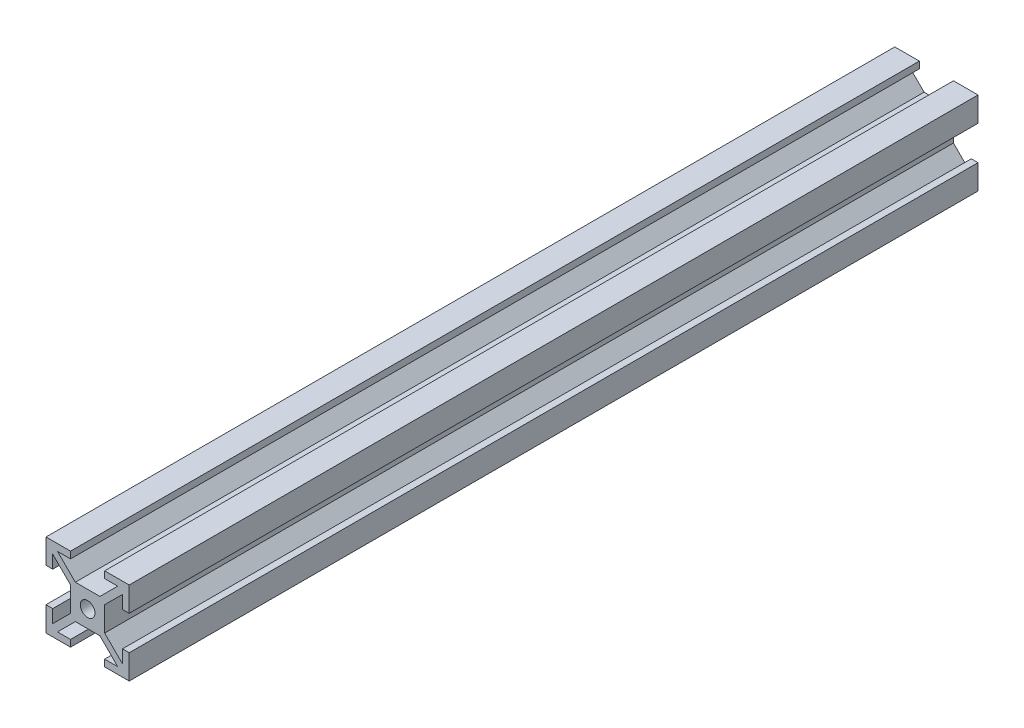
SolidWorks part; units mm, degrees
ref_plane "Front Plane" through (0, 0, 0) normal (0, 0, 1) x (1, 0, 0)
ref_plane "Top Plane" through (0, 0, 0) normal (0, 1, 0) x (1, 0, 0)
ref_plane "Right Plane" through (0, 0, 0) normal (1, 0, 0) x (0, 0, -1)
sketch "Sketch1" plane through (0, 0, 0) normal (0, 0, 1) x (1, 0, 0)
  line L0 (-8.38, 4.1) -> (-10, 4.1)
  line L1 (-2.9545, 4.1) -> (2.9545, 4.1)
  line L2 (-4.1, 2.9545) -> (-4.1, -2.9545)
  line L3 (-2.9545, -4.1) -> (2.9545, -4.1)
  line L4 (4.1, 2.9545) -> (4.1, -2.9545)
  line L5 (-4.1, 4.1) -> (4.1, -4.1) construction
  line L6 (-4.1, -4.1) -> (4.1, 4.1) construction
  line L7 (-10, 10) -> (-4.1, 10)
  line L8 (-10, 10) -> (-10, 4.1)
  line L9 (-10, -10) -> (-4.1, -10)
  line L10 (10, 10) -> (10, 4.1)
  line L11 (-10, 10) -> (10, -10) construction
  line L12 (-10, -10) -> (10, 10) construction
  line L13 (-7.2345, 8.38) -> (-4.1, 8.38)
  line L14 (-8.38, 7.2345) -> (-8.38, 4.1)
  line L15 (-7.2345, -8.38) -> (-4.1, -8.38)
  line L16 (8.38, 7.2345) -> (8.38, 4.1)
  line L17 (-8.38, 8.38) -> (8.38, -8.38) construction
  line L18 (-8.38, -8.38) -> (8.38, 8.38) construction
  line L19 (-4.1, 8.38) -> (-4.1, 10)
  line L20 (4.1, 10) -> (4.1, 8.38)
  line L21 (8.38, 4.1) -> (10, 4.1)
  line L22 (-8.38, -4.1) -> (-10, -4.1)
  line L23 (-4.1, -8.38) -> (-4.1, -10)
  line L24 (8.38, -4.1) -> (10, -4.1)
  line L25 (4.1, -8.38) -> (4.1, -10)
  line L26 (-5.464, 5.464) -> (-4.8912, 6.0368) construction
  line L27 (-4.1, 2.9545) -> (-8.38, 7.2345)
  line L28 (-2.9545, 4.1) -> (-7.2345, 8.38)
  line L29 (0, 11.3108) -> (0, -17.1823) construction
  line L30 (-16.7028, 0) -> (14.4032, 0) construction
  line L31 (-2.9545, -4.1) -> (-7.2345, -8.38)
  line L32 (-4.1, -2.9545) -> (-8.38, -7.2345)
  line L33 (2.9545, -4.1) -> (7.2345, -8.38)
  line L34 (4.1, -2.9545) -> (8.38, -7.2345)
  line L35 (4.1, 2.9545) -> (8.38, 7.2345)
  line L36 (2.9545, 4.1) -> (7.2345, 8.38)
  line L37 (4.1, 8.38) -> (7.2345, 8.38)
  line L38 (4.1, 10) -> (10, 10)
  line L39 (-8.38, -4.1) -> (-8.38, -7.2345)
  line L40 (-10, -4.1) -> (-10, -10)
  line L41 (8.38, -4.1) -> (8.38, -7.2345)
  line L42 (10, -4.1) -> (10, -10)
  line L43 (4.1, -8.38) -> (7.2345, -8.38)
  line L44 (4.1, -10) -> (10, -10)
  circle A0 centre (0, 0) radius 1.77
  point P0 (0, 0)
  point P6 (0, 0)
  dimension "D5" = 3.54
  dimension "D1" = 8.2
  dimension "D2" = 20
  dimension "D3" = 8.2
  dimension "D4" = 20
  dimension "D6" = 16.76
  dimension "D7" = 16.76
  dimension "D8" = 0.81
  dimension "D9" = 135
  dimension "D10" = 7.7696
  dimension "D11" = 5.0536
extrude "Boss-Extrude1" add sketch "Sketch1" along normal blind 204
